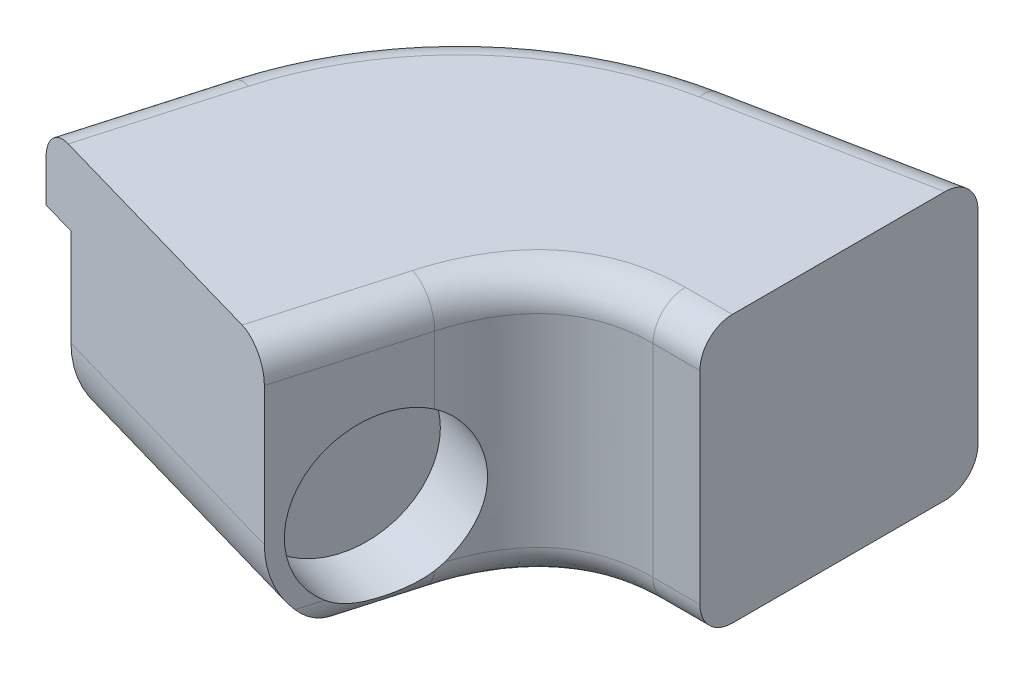
SolidWorks part; units mm, degrees
ref_plane "Спереди" through (0, 0, 0) normal (0, 0, 1) x (1, 0, 0)
ref_plane "Сверху" through (0, 0, 0) normal (0, 1, 0) x (1, 0, 0)
ref_plane "Справа" through (0, 0, 0) normal (1, 0, 0) x (0, 0, -1)
sketch "Эскиз1" plane through (0, 0, 0) normal (0, 1, 0) x (1, 0, 0)
  line L0 (-26.4853, 55.6595) -> (-39.5083, 53.069)
  line L4 (-55.8479, 29.0519) -> (-52.0028, 27.9493)
  line L5 (-52.0028, 27.9493) -> (-48.6952, 39.4844)
  line L6 (-48.6952, 39.4844) -> (-39.6579, 36.893)
  line L7 (-39.6579, 36.893) -> (-42.9655, 25.3579)
  line L8 (-42.9655, 25.3579) -> (-39.1205, 24.2554)
  line L9 (-39.1205, 24.2554) -> (-36.7776, 32.4261)
  line L10 (-29.3807, 38.5) -> (-26.4853, 38.5)
  line L11 (-26.4853, 38.5) -> (-26.4853, 55.6595)
  line L13 (-36.297, 32.2883) -> (-36.7776, 32.4261)
  line L17 (-36.7776, 32.4261) -> (-35.0359, 38.5) construction
  line L18 (-35.0359, 38.5) -> (-29.3807, 38.5) construction
  line L19 (-55.53, 38.3234) -> (-52.0151, 50.5813) construction
  line L20 (-39.5083, 53.069) -> (-52.0151, 50.5813) construction
  line L21 (-55.53, 38.3234) -> (-58.0107, 29.672)
  line L22 (-58.0107, 29.672) -> (-55.8479, 29.0519)
  arc A4 (-39.5083, 53.069) -> (-55.53, 38.3234) centre (-35.4286, 32.5594) ccw
  spline S0 degree 2 poles (-36.7776, 32.4261) (-35.0359, 38.5) (-29.3807, 38.5) knots 0 0 0 1 1 1
  point P3 (0, 0)
  point P4 (0, 0)
  point P7 (0, 0)
  point P8 (0, 0)
  point P22 (0, 0)
  point P26 (0, 0)
  point P28 (0, 0)
  point P31 (0, 0)
  point P32 (0, 0)
  point P33 (0, 0)
  point P34 (0, 0)
extrude "Бобышка-Вытянуть1" add sketch "Эскиз1" against normal blind 6 and the other way blind 10.5
fillet "Скругление1" radius 2 12 edges at (-37.949, -6, -28.3407) (-37.949, 10.5, -28.3407) (-27.933, -6, -38.5) (-27.933, 10.5, -38.5) (-32.9968, -6, -54.3642) (-32.9968, 10.5, -54.3642) (-49.5898, -6, -47.9461) (-49.5898, 10.5, -47.9461) (-56.7703, -6, -33.9977) (-56.7703, 10.5, -33.9977)
sketch "Эскиз2" plane through (-55.4573, 0, -15.9021) normal (-0.9613, 0, -0.2756) x (-0.2756, 0, 0.9613)
  line L0 (-12.5327, -6) -> (-18.5327, -6)
  line L2 (-18.5327, -6) -> (-18.5327, 0)
  line L3 (-12.5327, 0) -> (-12.5327, -6)
  circle A0 centre (-18.5327, 0) radius 5
  circle A1 centre (-18.5327, 0) radius 6
  point P3 (0, 0)
  point P9 (0, 0)
extrude "Вырез-Вытянуть1" cut sketch "Эскиз2" against normal through all both and the other way through all
sketch "Эскиз4" plane through (-61.4652, 0, -17.6249) normal (-0.9613, 0, -0.2756) x (-0.2756, 0, 0.9613)
  line L0 (-16.0327, 6) -> (-12.5327, 6)
  line L1 (-12.5327, 8.5) -> (-12.5327, 0) construction
  line L2 (-12.5327, 6) -> (-12.5327, 2.5)
  line L3 (-24.5327, -2.5) -> (-24.5327, -6)
  line L4 (-24.5327, -6) -> (-21.0327, -6)
  line L5 (-12.5327, 2.5) -> (-12.5327, -6)
  line L6 (-12.5327, -6) -> (-21.0327, -6)
  arc A0 (-16.0327, 6) -> (-24.5327, -2.5) centre (-18.5327, 0) ccw
extrude "Вырез-Вытянуть2" cut sketch "Эскиз4" against normal blind 2.25
sketch "Эскиз5" plane through (-46.42, 0, -13.3107) normal (-0.9613, 0, -0.2756) x (-0.2756, 0, 0.9613)
  line L0 (-24.5327, 10.5) -> (-24.5327, -6)
  line L1 (-24.5327, 10.5) -> (-12.5327, 10.5)
  line L2 (-24.5327, -6) -> (-18.5327, -6)
  line L4 (-12.5327, 0) -> (-12.5327, 10.5)
  arc A0 (-18.5327, -6) -> (-12.5327, 0) centre (-18.5327, 0) ccw
extrude "Бобышка-Вытянуть3" add sketch "Эскиз5" along normal up to surface (9.4015 mm away) up to face at (-51.7272, 0, -28.9106)
